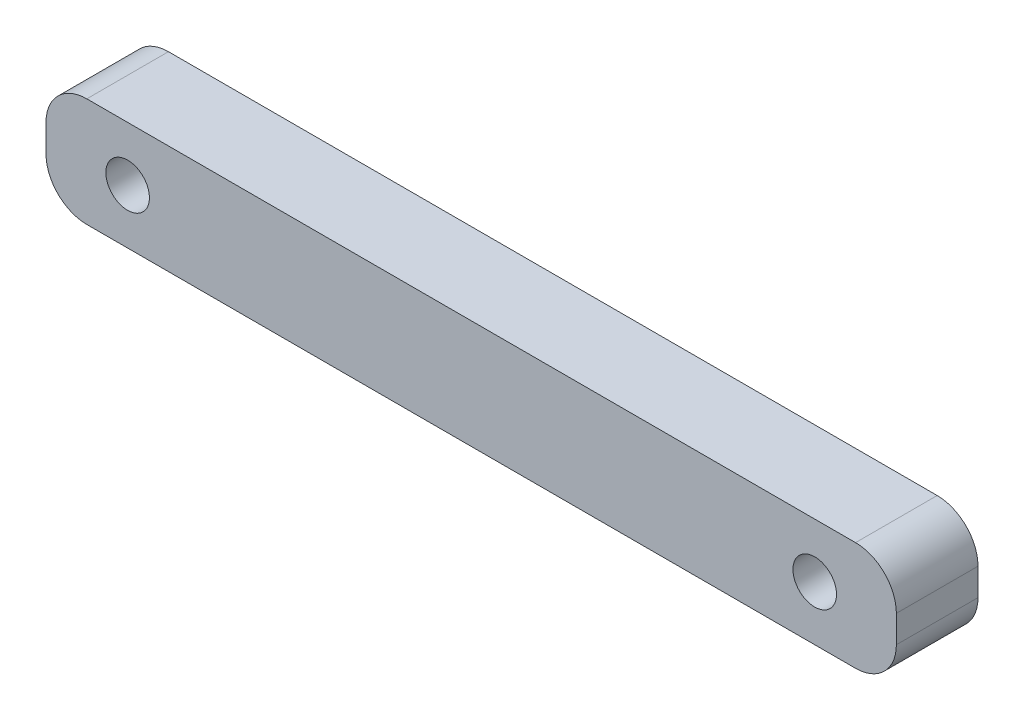
SolidWorks part; units mm, degrees
ref_plane "Front" through (0, 0, 0) normal (0, 0, 1) x (1, 0, 0)
ref_plane "Top" through (0, 0, 0) normal (0, 1, 0) x (1, 0, 0)
ref_plane "Right" through (0, 0, 0) normal (1, 0, 0) x (0, 0, -1)
sketch "Sketch1" plane through (0, 0, 0) normal (0, 0, 1) x (1, 0, 0)
  line L1 (0, 0) -> (62.5, 0)
  line L2 (0, 0) -> (0, -8)
  line L3 (0, -8) -> (62.5, -8)
  line L4 (62.5, 0) -> (62.5, -8)
  dimension "D1" = 8
  dimension "D2" = 62.5
extrude "Boss-Extrude1" add sketch "Sketch1" along normal blind 6
sketch "Sketch2" plane through (0, 0, 6) normal (0, 0, 1) x (1, 0, 0)
  line L0 (0, 0) -> (0, -8) construction
  line L1 (62.5, -8) -> (62.5, 0) construction
  line L2 (0, -8) -> (62.5, -8) construction
  circle A0 centre (56.5, -4) radius 1.6
  circle A1 centre (6, -4) radius 1.6
  dimension "D1" = 3.2
  dimension "D2" = 3.2
  dimension "D3" = 6
  dimension "D4" = 6
  dimension "D5" = 4
  dimension "D6" = 4
extrude "Cut-Extrude1" cut sketch "Sketch2" against normal through all
fillet "Fillet1" radius 3 4 edges at (62.5, -8, 3) (62.5, 0, 3) (0, -8, 3) (0, 0, 3)
